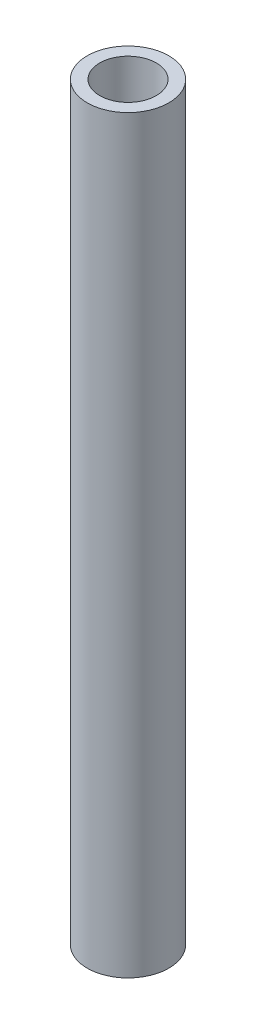
SolidWorks part; units mm, degrees
ref_plane "Front Plane" through (0, 0, 0) normal (0, 0, 1) x (1, 0, 0)
ref_plane "Top Plane" through (0, 0, 0) normal (0, 1, 0) x (1, 0, 0)
ref_plane "Right Plane" through (0, 0, 0) normal (1, 0, 0) x (0, 0, -1)
sketch "Sketch1" plane through (0, 0, 0) normal (0, 1, 0) x (1, 0, 0)
  circle A0 centre (0, 0) radius 16.5989
  circle A1 centre (0, 0) radius 11.5189
  dimension "D1" = 33.1978
  dimension "D2" = 5.08
extrude "Boss-Extrude1" add sketch "Sketch1" along normal mid plane 304.8
